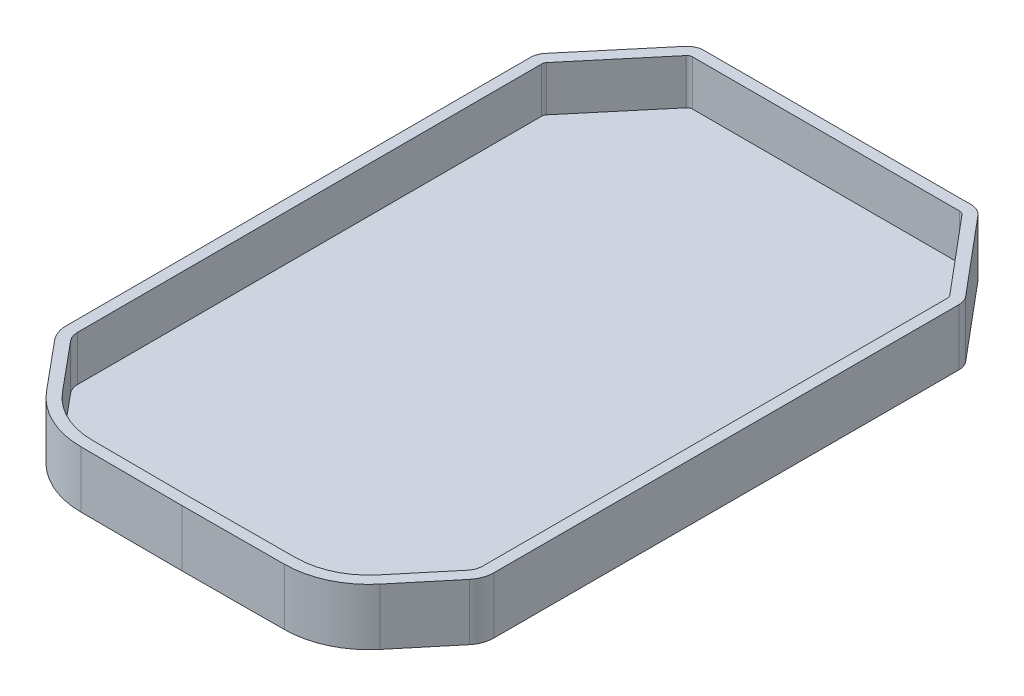
SolidWorks part; units mm, degrees
ref_plane "Ebene vorne" through (0, 0, 0) normal (0, 0, 1) x (1, 0, 0)
ref_plane "Ebene oben" through (0, 0, 0) normal (0, 1, 0) x (1, 0, 0)
ref_plane "Ebene rechts" through (0, 0, 0) normal (1, 0, 0) x (0, 0, -1)
sketch "Skizze1" plane through (0, 0, 0) normal (0, 1, 0) x (1, 0, 0)
  line L0 (-71.7828, 0) -> (65.2574, 0) construction
  line L1 (0, -55) -> (0, 55) construction
  line L2 (0, 50.8602) -> (0, -44.8504) construction
  line L4 (0, -75.745) -> (-24.9998, -75.6418)
  line L5 (-24.9998, -75.6418) -> (-37.7921, -60.2679)
  line L6 (-37.7921, -60.2679) -> (-37.8558, 24.7321)
  line L7 (-37.8558, 24.7321) -> (-25, 40.053)
  line L8 (-25, 40.053) -> (0, 40.053)
  line L9 (0, 40.053) -> (0, -75.745)
  dimension "D1" = 85
  dimension "D2" = 20
  dimension "D3" = 130
  dimension "D4" = 25
  dimension "D5" = 130
  dimension "D6" = 115.798
extrude "Aufsatz-Linear austragen1" add sketch "Skizze1" along normal blind 10
mirror "Spiegeln1" about plane through (0, 0, 0) normal (1, 0, 0) of "Aufsatz-Linear austragen1"
fillet "Verrundung11" radius 15 2 edges at (-24.9998, 5, 75.6418) (24.9998, 5, 75.6418)
fillet "Verrundung12" radius 5 2 edges at (37.7921, 5, 60.2679) (-37.7921, 5, 60.2679)
fillet "Verrundung13" radius 3 2 edges at (-25, 5, -40.053) (25, 5, -40.053)
fillet "Verrundung14" radius 3 2 edges at (37.8558, 5, -24.7321) (-37.8558, 5, -24.7321)
shell "Wandung1" thickness 2
